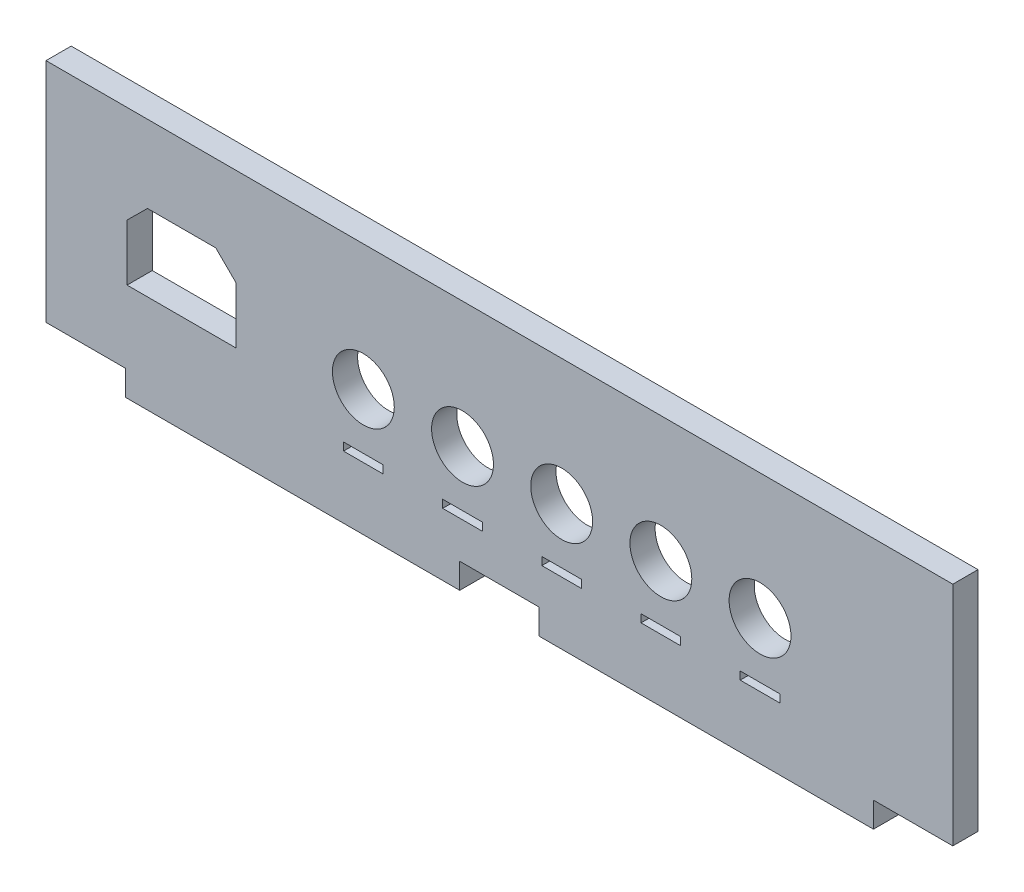
SolidWorks part; units mm, degrees
ref_plane "Front Plane" through (0, 0, 0) normal (0, 0, 1) x (1, 0, 0)
ref_plane "Top Plane" through (0, 0, 0) normal (0, 1, 0) x (1, 0, 0)
ref_plane "Right Plane" through (0, 0, 0) normal (1, 0, 0) x (0, 0, -1)
sketch "Sketch1" plane through (0, 0, 0) normal (0, 0, 1) x (1, 0, 0)
  line L1 (-114.3, -31.75) -> (114.3, -31.75)
  line L2 (-114.3, -31.75) -> (-114.3, 31.75)
  line L3 (-114.3, 31.75) -> (114.3, 31.75)
  line L4 (114.3, -31.75) -> (114.3, 31.75)
  line L5 (-114.3, -31.75) -> (114.3, 31.75) construction
  line L6 (-114.3, 31.75) -> (114.3, -31.75) construction
  point P0 (0, 0)
  dimension "D1" = 63.5
  dimension "D2" = 228.6
extrude "Boss-Extrude1" add sketch "Sketch1" along normal blind 6.35
sketch "Sketch3" plane through (0, 0, 6.35) normal (0, 0, 1) x (1, 0, 0)
  line L0 (-114.3, -31.75) -> (114.3, -31.75) construction
  line L1 (-114.3, -31.75) -> (-94.3, -31.75)
  line L2 (-114.3, -31.75) -> (-114.3, -25.4)
  line L3 (-114.3, -25.4) -> (-94.3, -25.4)
  line L4 (-94.3, -31.75) -> (-94.3, -25.4)
  line L5 (-10, -31.75) -> (10, -31.75)
  line L6 (-10, -31.75) -> (-10, -25.4)
  line L7 (-10, -25.4) -> (10, -25.4)
  line L8 (10, -31.75) -> (10, -25.4)
  line L9 (-114.3, 31.75) -> (-114.3, -31.75) construction
  line L10 (114.3, -31.75) -> (94.3, -31.75)
  line L11 (114.3, -31.75) -> (114.3, -25.4)
  line L12 (114.3, -25.4) -> (94.3, -25.4)
  line L13 (94.3, -31.75) -> (94.3, -25.4)
  line L14 (-4.3, -16) -> (-4.3, -14)
  line L15 (-39.3, -16) -> (-29.3, -16)
  line L16 (-39.3, -16) -> (-39.3, -14)
  line L17 (-39.3, -14) -> (-29.3, -14)
  line L18 (-29.3, -16) -> (-29.3, -14)
  line L19 (-39.3, -16) -> (-29.3, -14) construction
  line L20 (-39.3, -14) -> (-29.3, -16) construction
  line L21 (-14.3, -16) -> (-4.3, -16)
  line L22 (-14.3, -16) -> (-14.3, -14)
  line L23 (-14.3, -14) -> (-4.3, -14)
  line L24 (20.7, -16) -> (20.7, -14)
  line L25 (10.7, -16) -> (20.7, -16)
  line L26 (10.7, -16) -> (10.7, -14)
  line L27 (10.7, -14) -> (20.7, -14)
  line L28 (45.7, -16) -> (45.7, -14)
  line L29 (35.7, -16) -> (45.7, -16)
  line L30 (35.7, -16) -> (35.7, -14)
  line L31 (35.7, -14) -> (45.7, -14)
  line L32 (70.7, -16) -> (70.7, -14)
  line L33 (60.7, -16) -> (70.7, -16)
  line L34 (60.7, -16) -> (60.7, -14)
  line L35 (60.7, -14) -> (70.7, -14)
  circle A0 centre (-34.3, 0) radius 7.8
  circle A4 centre (-9.3, 0) radius 7.8
  circle A5 centre (15.7, 0) radius 7.8
  circle A6 centre (40.7, 0) radius 7.8
  circle A7 centre (65.7, 0) radius 7.8
  point P15 (0, -25.4)
  point P22 (-114.3, 0)
  point P23 (-34.3, -15)
  point P53 (-9.3, -14)
  dimension "D3" = 15.6
  dimension "D4" = 5
  dimension "D1" = 6.35
  dimension "D2" = 20
  dimension "80" = 80
  dimension "D5" = 25
  dimension "D6" = 10
  dimension "D7" = 2
  dimension "D8" = 15
  dimension "D10" = 25
  dimension "D9" = 5
extrude "Cut-Extrude1" cut sketch "Sketch3" against normal through all
sketch "Sketch5" plane through (0, 0, 0) normal (0, 0, -1) x (-1, 0, 0)
  line L0 (66.8614, -6.5395) -> (66.8614, 6.9605)
  line L1 (66.8614, 6.9605) -> (71.7114, 11.7605)
  line L2 (71.7114, 11.7605) -> (88.5114, 11.7605)
  line L3 (88.5114, 11.7605) -> (93.3614, 6.9605)
  line L4 (93.3614, 6.9605) -> (93.3614, -6.5395) construction
  line L5 (93.3614, -6.5395) -> (66.8614, -6.5395)
  line L6 (80.1114, 11.7605) -> (80.1114, -6.5395) construction
  line L7 (51.335, -15.589) -> (109.0591, -15.589) construction
  line L8 (51.335, -15.589) -> (51.335, 16.1153)
  line L9 (51.335, 16.1153) -> (109.0591, 16.1153)
  line L10 (109.0591, -15.589) -> (109.0591, 16.1153) construction
  line L12 (93.8614, -7.0395) -> (66.3614, -7.0395)
  line L13 (66.3614, -7.0395) -> (66.3614, 7.1691)
  line L14 (66.3614, 7.1691) -> (71.5058, 12.2605)
  line L15 (71.5058, 12.2605) -> (88.717, 12.2605)
  line L16 (88.717, 12.2605) -> (93.8614, 7.1691)
  line L17 (93.8614, 7.1691) -> (93.8614, -7.0395)
  point P2 (80.1114, -8.3395)
  point P7 (80.1114, -6.5395)
  dimension "D1" = 0.5
extrude "Cut-Extrude2" cut sketch "Sketch5" against normal through all
